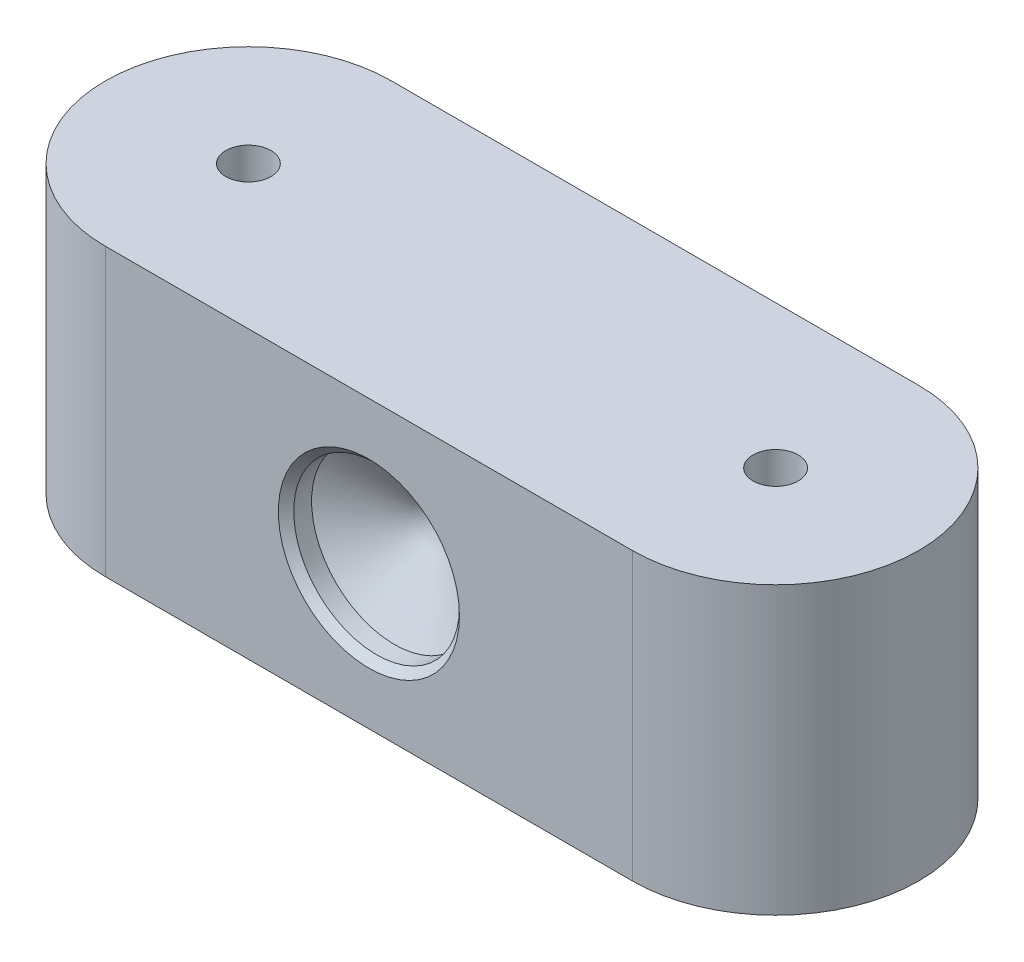
SolidWorks part; units mm, degrees
ref_plane "Front Plane" through (0, 0, 0) normal (0, 0, 1) x (1, 0, 0)
ref_plane "Top Plane" through (0, 0, 0) normal (0, 1, 0) x (1, 0, 0)
ref_plane "Right Plane" through (0, 0, 0) normal (1, 0, 0) x (0, 0, -1)
sketch "Sketch1" plane through (0, 0, 0) normal (0, 1, 0) x (1, 0, 0)
  line L0 (-35, 0) -> (35, 0) construction
  line L1 (-35, 19) -> (35, 19)
  line L2 (-35, -19) -> (35, -19)
  arc A0 (-35, 19) -> (-35, -19) centre (-35, 0) ccw
  arc A1 (35, -19) -> (35, 19) centre (35, 0) ccw
  circle A2 centre (-35, 0) radius 3
  circle A3 centre (35, 0) radius 3
  point P2 (0, 0)
  dimension "D1" = 19
  dimension "D3" = 6
  dimension "D2" = 70
extrude "Boss-Extrude1" add sketch "Sketch1" along normal mid plane 38
hole_wizard "M24x2.0 Tapped Hole1" positions "Sketch2" profile "Sketch3" tap size "M24x2.0" standard "ANSI Metric"
sketch "Sketch2" plane through (0, 0, 19) normal (0, 0, 1) x (1, 0, 0)
  point P0 (0, 0)
sketch "Sketch3" plane through (0, 0, 19) normal (1, 0, 0) x (0, -1, 0)
  line L0 (0, 0) -> (0, 10)
  line L1 (0, 10) -> (11, 3.3905)
  line L2 (11, 3.3905) -> (11, 1.025)
  line L3 (11, 1.025) -> (12.025, 0)
  line L5 (12.025, 0) -> (0, 0)
  line L6 (-11, 1.025) -> (-12.025, 0) construction
  line L10 (0, 10) -> (-11, 3.3905) construction
  line L11 (0, -6.35) -> (0, 107.95) construction
  dimension "Tap Drill Dia." = 22
  dimension "Tap Drill Depth" = 10
  dimension "Near C'Sink Dia." = 24.05
  dimension "Near C'Sink Angle" = 90
  dimension "Drill Angle" = 118
cosmetic thread "Hole Thread1"
